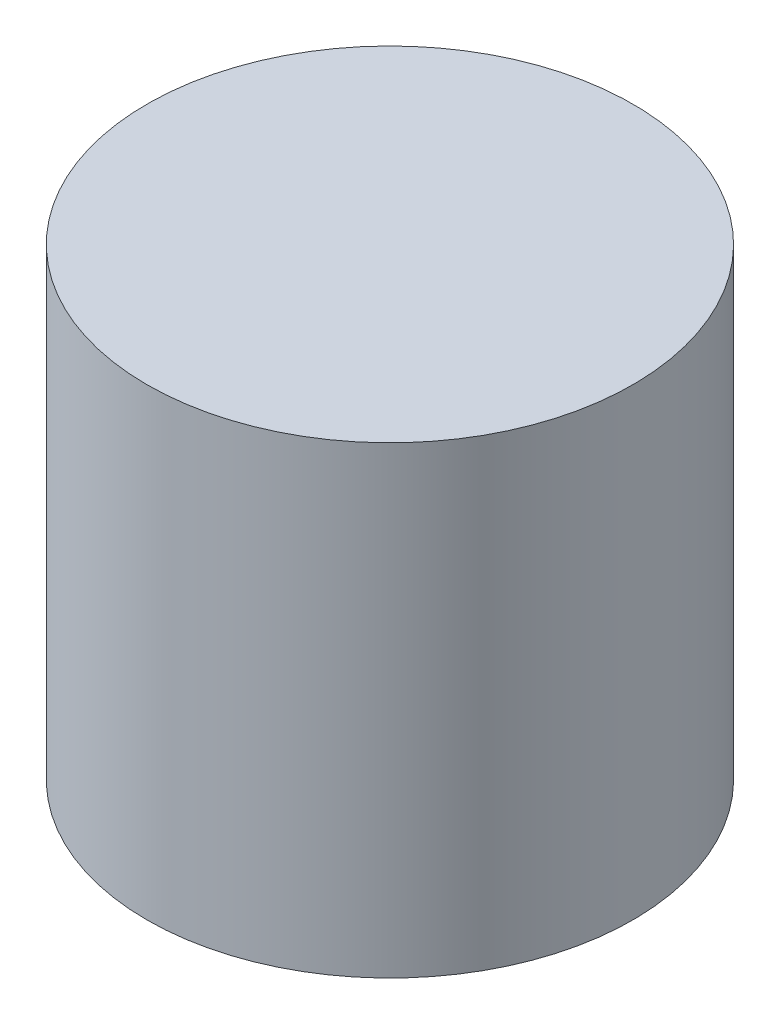
SolidWorks part; units mm, degrees
ref_plane "Alzado" through (0, 0, 0) normal (0, 0, 1) x (1, 0, 0)
ref_plane "Planta" through (0, 0, 0) normal (0, 1, 0) x (1, 0, 0)
ref_plane "Vista lateral" through (0, 0, 0) normal (1, 0, 0) x (0, 0, -1)
sketch "Croquis1" plane through (0, 0, 0) normal (1, 0, 0) x (0, 0, -1)
  line L0 (0, 318.8321) -> (0, -619.5927) construction
  line L1 (-444.7635, 0) -> (617.658, 0) construction
  line L2 (0, 45) -> (-260, 45)
  line L3 (-260, 45) -> (-260, -451)
  line L4 (-260, -451) -> (-56, -451)
  line L5 (-56, -451) -> (-56, -551)
  line L6 (-56, -551) -> (0, -551)
  line L7 (0, 45) -> (0, -551)
  dimension "D1" = 260
  dimension "D2" = 45
  dimension "D3" = 496
  dimension "D4" = 56
  dimension "D5" = 100
revolve "Revolución1" add sketch "Croquis1" angle 360 about L7
